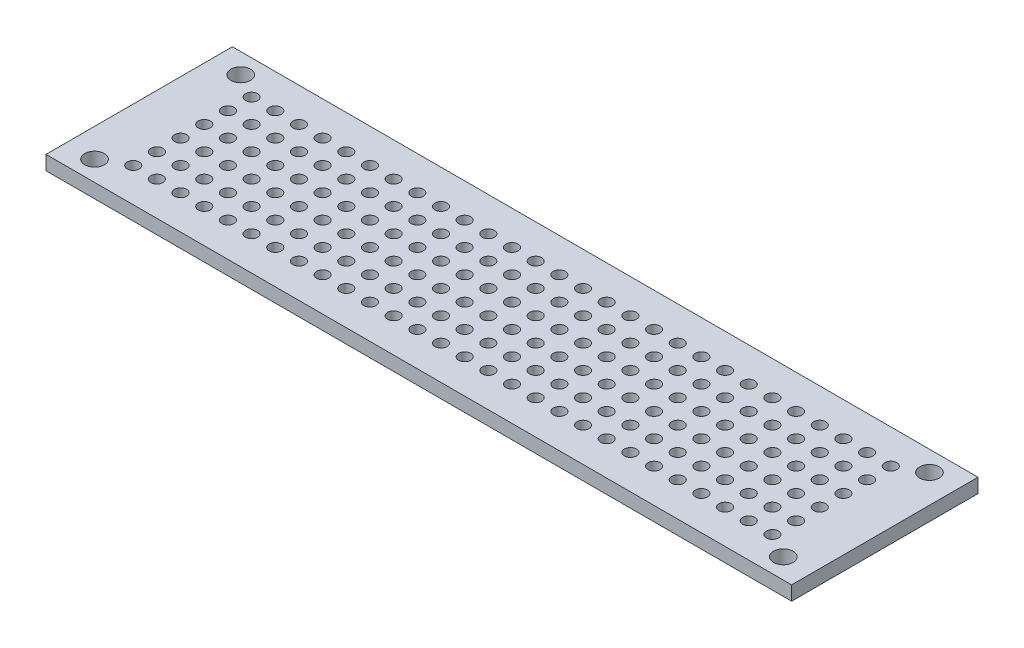
SolidWorks part; units mm, degrees
ref_plane "Front Plane" through (0, 0, 0) normal (0, 0, 1) x (1, 0, 0)
ref_plane "Top Plane" through (0, 0, 0) normal (0, 1, 0) x (1, 0, 0)
ref_plane "Right Plane" through (0, 0, 0) normal (1, 0, 0) x (0, 0, -1)
sketch "Sketch1" plane through (0, 0, 0) normal (0, 1, 0) x (1, 0, 0)
  line L1 (0, 0) -> (80, 0)
  line L2 (0, 0) -> (0, 20)
  line L3 (0, 20) -> (80, 20)
  line L9 (80, 20) -> (80, 0)
  dimension "D1" = 80
  dimension "D2" = 20
extrude "Boss-Extrude1" add sketch "Sketch1" along normal mid plane 1.524
hole_wizard "Ø1.3 (1.3) Diameter Hole1" positions "Sketch2" profile "Sketch3" hole size "Ø1.3" standard "ANSI Metric" end condition up to next
sketch "Sketch2" plane through (0, 0.762, 0) normal (0, 1, 0) x (1, 0, 0)
  line L15 (40, 0) -> (40, 20) construction
  line L16 (0, 0) -> (80, 0) construction
  line L17 (80, 20) -> (0, 20) construction
  line L20 (0, 10) -> (80, 10) construction
  line L21 (0, 20) -> (0, 0) construction
  line L22 (80, 0) -> (80, 20) construction
  line L25 (5.71, 3.65) -> (8.25, 3.65) construction
  line L26 (5.71, 3.65) -> (5.71, 6.19) construction
  point P230 (5.71, 3.65)
  point P244 (8.25, 3.65)
  point P245 (10.79, 3.65)
  point P246 (13.33, 3.65)
  point P247 (15.87, 3.65)
  point P248 (18.41, 3.65)
  point P249 (20.95, 3.65)
  point P250 (23.49, 3.65)
  point P251 (26.03, 3.65)
  point P252 (28.57, 3.65)
  point P253 (31.11, 3.65)
  point P254 (33.65, 3.65)
  point P255 (36.19, 3.65)
  point P256 (38.73, 3.65)
  point P257 (41.27, 3.65)
  point P258 (43.81, 3.65)
  point P259 (46.35, 3.65)
  point P260 (48.89, 3.65)
  point P261 (51.43, 3.65)
  point P262 (53.97, 3.65)
  point P263 (56.51, 3.65)
  point P264 (59.05, 3.65)
  point P265 (61.59, 3.65)
  point P266 (64.13, 3.65)
  point P274 (8.25, 6.19)
  point P275 (10.79, 6.19)
  point P276 (13.33, 6.19)
  point P277 (15.87, 6.19)
  point P278 (18.41, 6.19)
  point P279 (20.95, 6.19)
  point P280 (23.49, 6.19)
  point P281 (26.03, 6.19)
  point P282 (28.57, 6.19)
  point P283 (31.11, 6.19)
  point P284 (33.65, 6.19)
  point P285 (36.19, 6.19)
  point P286 (38.73, 6.19)
  point P287 (41.27, 6.19)
  point P288 (43.81, 6.19)
  point P289 (46.35, 6.19)
  point P290 (48.89, 6.19)
  point P291 (51.43, 6.19)
  point P292 (53.97, 6.19)
  point P293 (56.51, 6.19)
  point P294 (59.05, 6.19)
  point P295 (61.59, 6.19)
  point P296 (64.13, 6.19)
  point P304 (8.25, 8.73)
  point P305 (10.79, 8.73)
  point P306 (13.33, 8.73)
  point P307 (15.87, 8.73)
  point P308 (18.41, 8.73)
  point P309 (20.95, 8.73)
  point P310 (23.49, 8.73)
  point P311 (26.03, 8.73)
  point P312 (28.57, 8.73)
  point P313 (31.11, 8.73)
  point P314 (33.65, 8.73)
  point P315 (36.19, 8.73)
  point P316 (38.73, 8.73)
  point P317 (41.27, 8.73)
  point P318 (43.81, 8.73)
  point P319 (46.35, 8.73)
  point P320 (48.89, 8.73)
  point P321 (51.43, 8.73)
  point P322 (53.97, 8.73)
  point P323 (56.51, 8.73)
  point P324 (59.05, 8.73)
  point P325 (61.59, 8.73)
  point P326 (64.13, 8.73)
  point P334 (8.25, 11.27)
  point P335 (10.79, 11.27)
  point P336 (13.33, 11.27)
  point P337 (15.87, 11.27)
  point P338 (18.41, 11.27)
  point P339 (20.95, 11.27)
  point P340 (23.49, 11.27)
  point P341 (26.03, 11.27)
  point P342 (28.57, 11.27)
  point P343 (31.11, 11.27)
  point P344 (33.65, 11.27)
  point P345 (36.19, 11.27)
  point P346 (38.73, 11.27)
  point P347 (41.27, 11.27)
  point P348 (43.81, 11.27)
  point P349 (46.35, 11.27)
  point P350 (48.89, 11.27)
  point P351 (51.43, 11.27)
  point P352 (53.97, 11.27)
  point P353 (56.51, 11.27)
  point P354 (59.05, 11.27)
  point P355 (61.59, 11.27)
  point P356 (64.13, 11.27)
  point P364 (8.25, 13.81)
  point P365 (10.79, 13.81)
  point P366 (13.33, 13.81)
  point P367 (15.87, 13.81)
  point P368 (18.41, 13.81)
  point P369 (20.95, 13.81)
  point P370 (23.49, 13.81)
  point P371 (26.03, 13.81)
  point P372 (28.57, 13.81)
  point P373 (31.11, 13.81)
  point P374 (33.65, 13.81)
  point P375 (36.19, 13.81)
  point P376 (38.73, 13.81)
  point P377 (41.27, 13.81)
  point P378 (43.81, 13.81)
  point P379 (46.35, 13.81)
  point P380 (48.89, 13.81)
  point P381 (51.43, 13.81)
  point P382 (53.97, 13.81)
  point P383 (56.51, 13.81)
  point P384 (59.05, 13.81)
  point P385 (61.59, 13.81)
  point P386 (64.13, 13.81)
  point P394 (8.25, 16.35)
  point P395 (10.79, 16.35)
  point P396 (13.33, 16.35)
  point P397 (15.87, 16.35)
  point P398 (18.41, 16.35)
  point P399 (20.95, 16.35)
  point P400 (23.49, 16.35)
  point P401 (26.03, 16.35)
  point P402 (28.57, 16.35)
  point P403 (31.11, 16.35)
  point P404 (33.65, 16.35)
  point P405 (36.19, 16.35)
  point P406 (38.73, 16.35)
  point P407 (41.27, 16.35)
  point P408 (43.81, 16.35)
  point P409 (46.35, 16.35)
  point P410 (48.89, 16.35)
  point P411 (51.43, 16.35)
  point P412 (53.97, 16.35)
  point P413 (56.51, 16.35)
  point P414 (59.05, 16.35)
  point P415 (61.59, 16.35)
  point P416 (64.13, 16.35)
  point P1054 (5.71, 6.19)
  point P1055 (5.71, 8.73)
  point P1056 (5.71, 11.27)
  point P1057 (5.71, 13.81)
  point P1058 (5.71, 16.35)
  point P1112 (66.67, 3.65)
  point P1113 (69.21, 3.65)
  point P1114 (71.75, 3.65)
  point P1115 (74.29, 3.65)
  point P1116 (66.67, 6.19)
  point P1117 (69.21, 6.19)
  point P1118 (71.75, 6.19)
  point P1119 (74.29, 6.19)
  point P1120 (66.67, 8.73)
  point P1121 (69.21, 8.73)
  point P1122 (71.75, 8.73)
  point P1123 (74.29, 8.73)
  point P1124 (66.67, 11.27)
  point P1125 (69.21, 11.27)
  point P1126 (71.75, 11.27)
  point P1127 (74.29, 11.27)
  point P1128 (66.67, 13.81)
  point P1129 (69.21, 13.81)
  point P1130 (71.75, 13.81)
  point P1131 (74.29, 13.81)
  point P1132 (66.67, 16.35)
  point P1133 (69.21, 16.35)
  point P1134 (71.75, 16.35)
  point P1135 (74.29, 16.35)
  dimension "D3" = 6
  dimension "D5" = 2.54
  dimension "D6" = 2.54
  dimension "D4" = 28
sketch "Sketch3" plane through (5.71, 0.762, -3.65) normal (1, 0, 0) x (0, 0, 1)
  line L0 (0, 0) -> (0, 1.524)
  line L1 (0, 1.524) -> (0.65, 1.524)
  line L2 (0.65, 1.524) -> (0.65, 0)
  line L5 (0.65, 0) -> (0, 0)
  line L11 (0, -6.35) -> (0, 107.95) construction
  dimension "Thru Hole Dia." = 1.3
  dimension "Thru Hole Depth" = 1.524
hole_wizard "Ø2.1 (2.1) Diameter Hole1" positions "Sketch4" profile "Sketch5" hole size "Ø2.1" standard "ANSI Metric" end condition up to next
sketch "Sketch4" plane through (0, 0.762, 0) normal (0, 1, 0) x (1, 0, 0)
  line L3 (3.048, 17.841) -> (76.952, 17.841) construction
  line L4 (3.048, 17.841) -> (3.048, 2.159) construction
  line L5 (3.048, 2.159) -> (76.952, 2.159) construction
  line L6 (76.952, 17.841) -> (76.952, 2.159) construction
  line L7 (0, 0) -> (80, 0) construction
  line L8 (80, 20) -> (0, 20) construction
  line L9 (0, 20) -> (0, 0) construction
  line L11 (80, 0) -> (80, 20) construction
  point P0 (3.048, 17.841)
  point P6 (76.952, 2.159)
  point P8 (76.952, 17.841)
  point P10 (3.048, 2.159)
  dimension "D1" = 2.159
  dimension "D2" = 2.159
  dimension "D3" = 3.048
  dimension "D4" = 3.048
sketch "Sketch5" plane through (3.048, 0.762, -17.841) normal (1, 0, 0) x (0, 0, 1)
  line L0 (0, 0) -> (0, 1.524)
  line L1 (0, 1.524) -> (1.05, 1.524)
  line L2 (1.05, 1.524) -> (1.05, 0)
  line L5 (1.05, 0) -> (0, 0)
  line L11 (0, -6.35) -> (0, 107.95) construction
  dimension "Thru Hole Dia." = 2.1
  dimension "Thru Hole Depth" = 1.524
equation "\"D2@Sketch4\"=\"D1@Sketch4\""
equation "\"D4@Sketch4\"=\"D3@Sketch4\""
